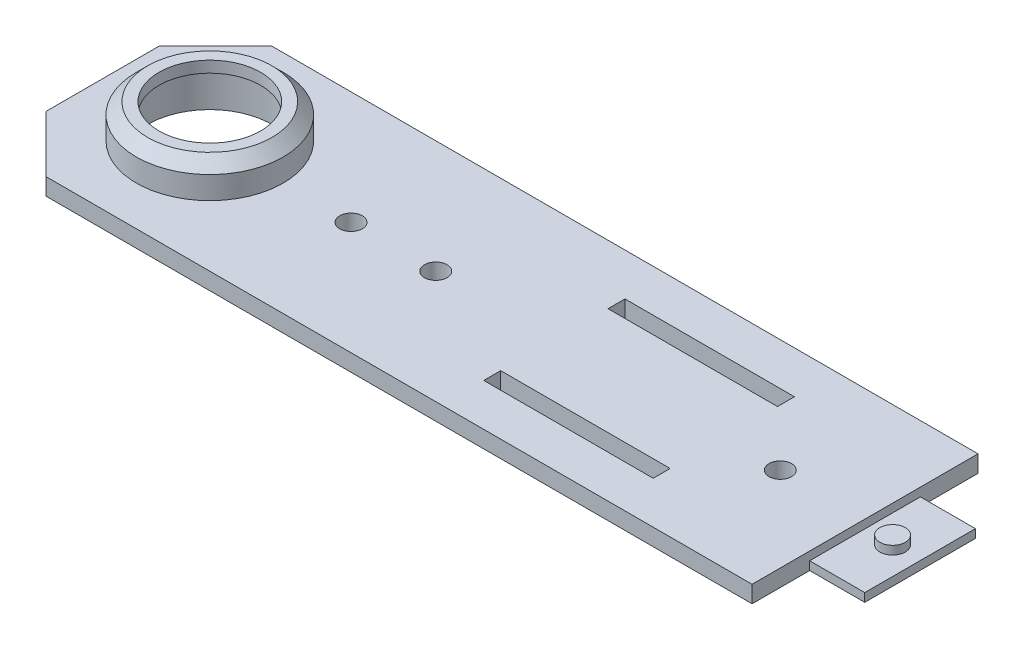
SolidWorks part; units mm, degrees
ref_plane "Alzado" through (0, 0, 0) normal (0, 0, 1) x (1, 0, 0)
ref_plane "Planta" through (0, 0, 0) normal (0, 1, 0) x (1, 0, 0)
ref_plane "Vista lateral" through (0, 0, 0) normal (1, 0, 0) x (0, 0, -1)
sketch "Croquis1" plane through (0, 0, 0) normal (0, 1, 0) x (1, 0, 0)
  line L1 (-67.5, -20) -> (67.5, -20)
  line L2 (-67.5, -20) -> (-67.5, 20)
  line L3 (-67.5, 20) -> (67.5, 20)
  line L4 (67.5, -20) -> (67.5, -9.8)
  line L5 (-67.5, -20) -> (67.5, 20) construction
  line L6 (-67.5, 20) -> (67.5, -20) construction
  line L10 (0, 0) -> (77.1384, 0) construction
  line L12 (12.5, 9.5) -> (42.5, 9.5)
  line L13 (12.5, 9.5) -> (12.5, 12.5)
  line L14 (12.5, 12.5) -> (42.5, 12.5)
  line L15 (42.5, 9.5) -> (42.5, 12.5)
  line L16 (12.5, 9.5) -> (42.5, 12.5) construction
  line L17 (12.5, 12.5) -> (42.5, 9.5) construction
  line L18 (12.5, -12.5) -> (42.5, -12.5)
  line L19 (12.5, -12.5) -> (12.5, -9.5)
  line L20 (12.5, -9.5) -> (42.5, -9.5)
  line L21 (42.5, -12.5) -> (42.5, -9.5)
  line L22 (12.5, -12.5) -> (42.5, -9.5) construction
  line L23 (12.5, -9.5) -> (42.5, -12.5) construction
  line L26 (67.5, 9.8) -> (67.5, 20)
  line L27 (67.5, 9.8) -> (77.25, 9.8)
  line L28 (77.25, 9.8) -> (77.25, -9.8)
  line L29 (77.25, -9.8) -> (67.5, -9.8)
  line L30 (-67.5, 0) -> (0, 0) construction
  circle A2 centre (-48.5, 0) radius 11
  circle A3 centre (-48.5, 0) radius 12.5 construction
  circle A4 centre (-23.5, 0) radius 2
  circle A5 centre (-8.5, 0) radius 2
  circle A6 centre (52.5, 0) radius 2
  point P0 (0, 0)
  point P6 (0, 0)
  point P9 (0, 0)
  point P19 (27.5, 11)
  point P35 (27.5, -11)
  dimension "D8" = 22
  dimension "D12" = 25
  dimension "D13" = 4
  dimension "D14" = 4
  dimension "D17" = 4
  dimension "D1" = 135
  dimension "D2" = 19.6
  dimension "D3" = 9.75
  dimension "D4" = 19
  dimension "D5" = 25
  dimension "D6" = 40
  dimension "D9" = 3
  dimension "D10" = 30
  dimension "D11" = 40
  dimension "D15" = 15
  dimension "D16" = 10
  dimension "D18" = 12.5
  dimension "D19" = 12.5
extrude "Saliente-Extruir1" add sketch "Croquis1" along normal blind 3
sketch "Croquis2" plane through (0, 3, 0) normal (0, 1, 0) x (1, 0, 0)
  circle A0 centre (-48.5, 0) radius 11
  circle A1 centre (-48.5, 0) radius 13
  dimension "D1" = 2
extrude "Saliente-Extruir2" add sketch "Croquis2" along normal blind 4
sketch "Croquis3" plane through (0, 7, 0) normal (0, 1, 0) x (1, 0, 0)
  circle A0 centre (-48.5, 0) radius 13
  circle A1 centre (-48.5, 0) radius 9
  dimension "D1" = 18
extrude "Saliente-Extruir3" add sketch "Croquis3" along normal blind 2
chamfer "Chaflán1" distance 2 angle 45 1 edges at (-48.5, 9, 13)
chamfer "Chaflán2" distance 10 angle 45 2 edges at (-67.5, 1.5, 20) (-67.5, 1.5, -20)
sketch "Croquis6" plane through (0, 3, 0) normal (0, 1, 0) x (1, 0, 0)
  line L0 (67.5, 0) -> (77.25, 0) construction
  line L1 (77.25, -9.8) -> (67.5, -9.8)
  line L2 (77.25, -9.8) -> (77.25, 9.8)
  line L3 (77.25, 9.8) -> (67.5, 9.8)
  line L4 (67.5, -9.8) -> (67.5, 9.8)
  circle A0 centre (72.375, 0) radius 2.25
  dimension "D1" = 4.5
extrude "Cortar-Extruir2" cut sketch "Croquis6" against normal blind 1.5
